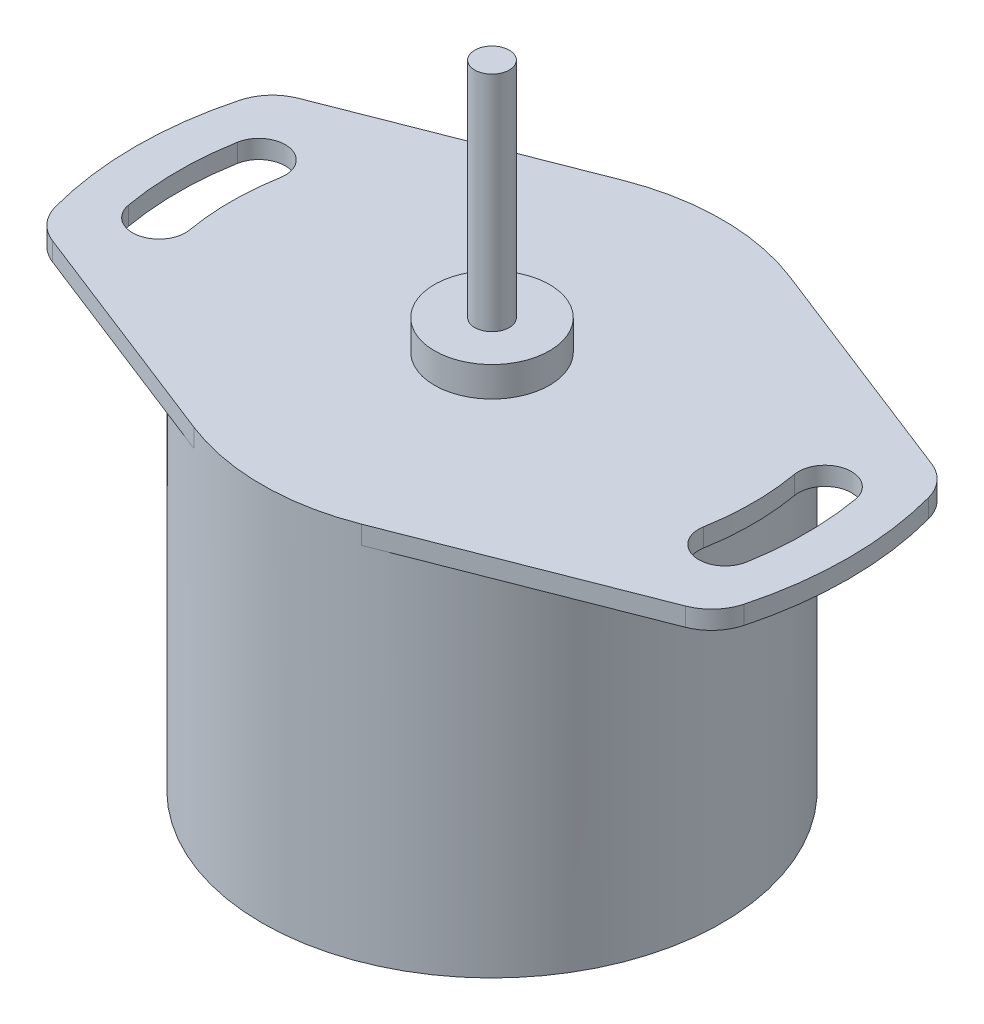
SolidWorks part; units mm, degrees
ref_plane "Front Plane" through (0, 0, 0) normal (0, 0, 1) x (1, 0, 0)
ref_plane "Top Plane" through (0, 0, 0) normal (0, 1, 0) x (1, 0, 0)
ref_plane "Right Plane" through (0, 0, 0) normal (1, 0, 0) x (0, 0, -1)
sketch "Sketch1" plane through (0, 0, 0) normal (0, 1, 0) x (1, 0, 0)
  circle A0 centre (0, 0) radius 10
  dimension "D1" = 20
extrude "Boss-Extrude1" add sketch "Sketch1" along normal blind 15.7
sketch "Sketch2" plane through (0, 0, 0) normal (0, -1, 0) x (1, 0, 0)
  circle A0 centre (0, 0) radius 3
  dimension "D1" = 6
extrude "Boss-Extrude2" add sketch "Sketch2" along normal blind 1.3
sketch "Sketch3" plane through (0, 15.7, 0) normal (0, 1, 0) x (1, 0, 0)
  line L0 (-14.6714, 5) -> (-3.6421, 9.3132)
  line L1 (3.6421, 9.3132) -> (14.6714, 5)
  line L2 (14.6714, -5) -> (3.6421, -9.3132)
  line L3 (-14.6714, -5) -> (-3.6421, -9.3132)
  line L4 (-12.5, 0) -> (12.5, 0) construction
  line L5 (-12.3101, 2.1706) -> (12.3101, -2.1706) construction
  line L6 (12.3101, 2.1706) -> (-12.3101, -2.1706) construction
  circle A0 centre (0, 0) radius 10 construction
  arc A1 (-14.6714, 5) -> (-14.6714, -5) centre (0, 0) ccw
  arc A2 (-3.6421, 9.3132) -> (3.6421, 9.3132) centre (0, 0) cw
  arc A3 (14.6714, 5) -> (14.6714, -5) centre (0, 0) cw
  arc A4 (3.6421, -9.3132) -> (-3.6421, -9.3132) centre (0, 0) cw
  arc A5 (-12.3101, 2.1706) -> (-12.3101, -2.1706) centre (0, 0) ccw construction
  arc A6 (-13.4426, 2.3703) -> (-13.4426, -2.3703) centre (0, 0) ccw
  arc A7 (-11.1776, 1.9709) -> (-11.1776, -1.9709) centre (0, 0) ccw
  arc A8 (-11.1776, 1.9709) -> (-13.4426, 2.3703) centre (-12.3101, 2.1706) ccw
  arc A9 (-13.4426, -2.3703) -> (-11.1776, -1.9709) centre (-12.3101, -2.1706) ccw
  arc A10 (12.3101, 2.1706) -> (12.3101, -2.1706) centre (0, 0) cw construction
  arc A11 (13.4426, -2.3703) -> (13.4426, 2.3703) centre (0, 0) ccw
  arc A12 (11.1776, -1.9709) -> (11.1776, 1.9709) centre (0, 0) ccw
  arc A13 (11.1776, -1.9709) -> (13.4426, -2.3703) centre (12.3101, -2.1706) ccw
  arc A14 (13.4426, 2.3703) -> (11.1776, 1.9709) centre (12.3101, 2.1706) ccw
  point P16 (-12.5, 0)
  point P22 (12.5, 0)
  dimension "D2" = 12.5
  dimension "D3" = 15.5
  dimension "D1" = 1.15
  dimension "D4" = 10
  dimension "D5" = 5
extrude "Boss-Extrude3" add sketch "Sketch3" along normal blind 0.8
fillet "Fillet1" radius 2 4 edges at (-14.6714, 16.1, -5) (14.6714, 16.1, -5) (14.6714, 16.1, 5) (-14.6714, 16.1, 5)
sketch "Sketch4" plane through (0, 16.5, 0) normal (0, 1, 0) x (1, 0, 0)
  circle A0 centre (0, 0) radius 2.5
  dimension "D1" = 5
extrude "Boss-Extrude4" add sketch "Sketch4" along normal blind 1.3
sketch "Sketch5" plane through (0, 17.8, 0) normal (0, 1, 0) x (1, 0, 0)
  circle A0 centre (0, 0) radius 0.75
  dimension "D1" = 1.5
extrude "Boss-Extrude5" add sketch "Sketch5" along normal blind 9.7
sketch "Sketch6" plane through (0, -1.3, 0) normal (0, -1, 0) x (1, 0, 0)
  circle A0 centre (0, 0) radius 0.75
  dimension "D1" = 1.5
extrude "Boss-Extrude6" add sketch "Sketch6" along normal blind 1.2
